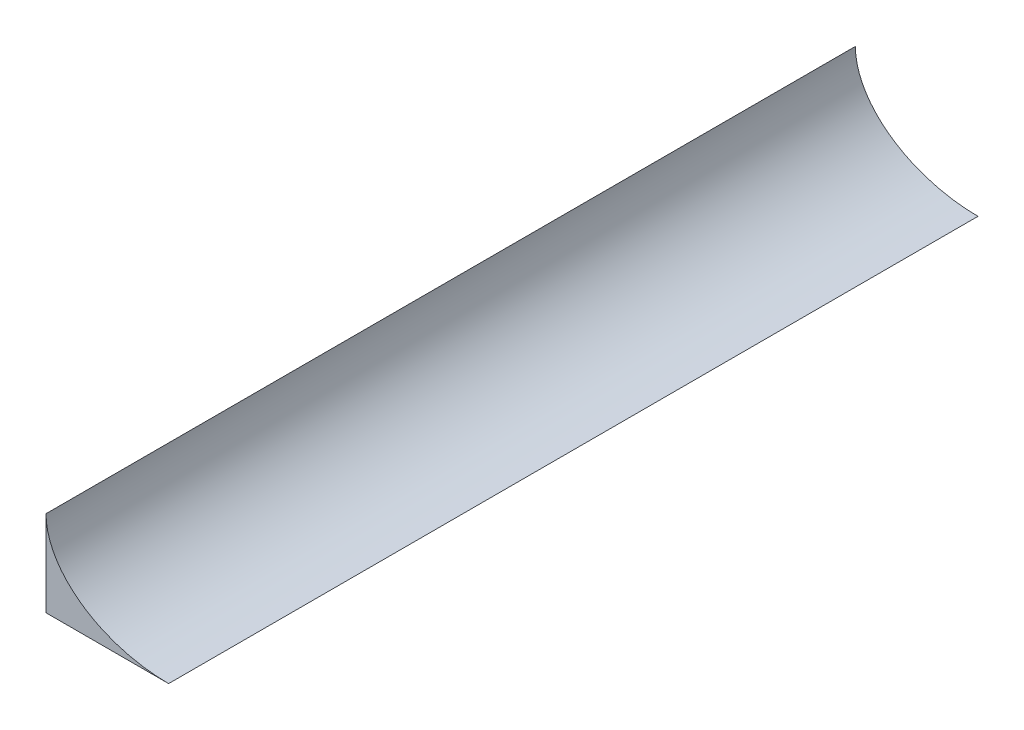
SolidWorks part; units mm, degrees
ref_plane "Front Plane" through (0, 0, 0) normal (0, 0, 1) x (1, 0, 0)
ref_plane "Top Plane" through (0, 0, 0) normal (0, 1, 0) x (1, 0, 0)
ref_plane "Right Plane" through (0, 0, 0) normal (1, 0, 0) x (0, 0, -1)
sketch "Sketch1" plane through (0, 0, 0) normal (0, 1, 0) x (1, 0, 0)
  line L1 (0, 0) -> (10, 0)
  line L2 (0, 0) -> (0, 66)
  line L3 (0, 66) -> (10, 66)
  line L4 (10, 0) -> (10, 66)
  dimension "D1" = 10
  dimension "D2" = 66
extrude "Boss-Extrude1" add sketch "Sketch1" along normal blind 7
sketch "Sketch2" plane through (0, 0, 0) normal (0, 0, 1) x (1, 0, 0)
  line L0 (0, 7) -> (10, 7)
  line L1 (10, 7) -> (10, 0)
  ellipse E0 centre (10, 7) end of major axis (0, 7) minor radius 7 (0, 7) -> (10, 0) ccw
extrude "Cut-Extrude1" cut sketch "Sketch2" against normal through all
